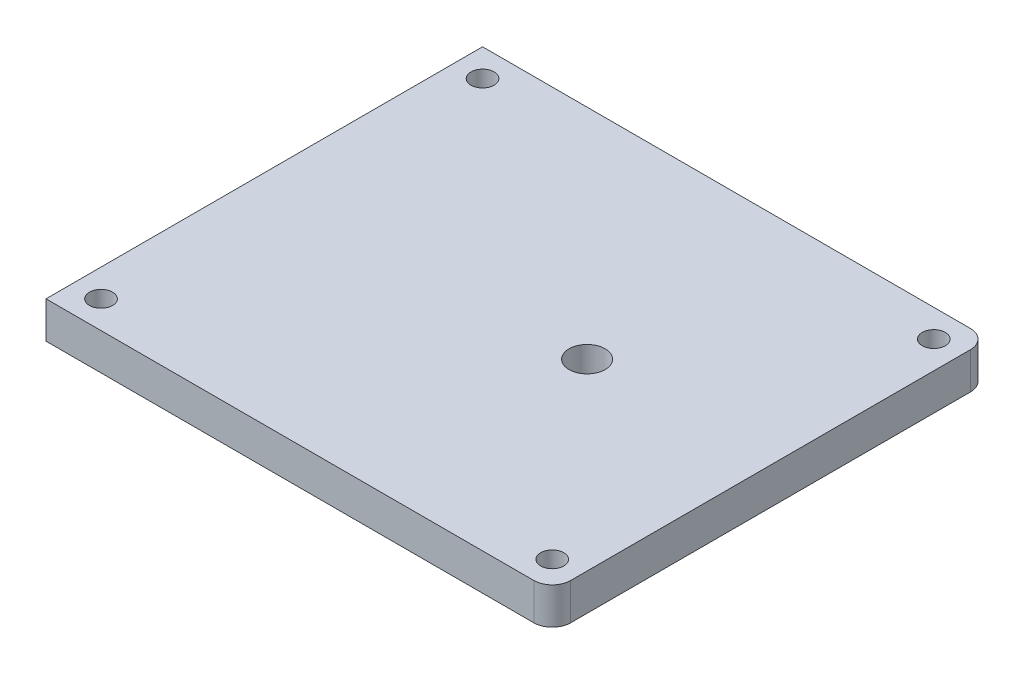
SolidWorks part; units mm, degrees
ref_plane "Front Plane" through (0, 0, 0) normal (0, 0, 1) x (1, 0, 0)
ref_plane "Top Plane" through (0, 0, 0) normal (0, 1, 0) x (1, 0, 0)
ref_plane "Right Plane" through (0, 0, 0) normal (1, 0, 0) x (0, 0, -1)
sketch "Sketch1" plane through (0, 0, 0) normal (0, 1, 0) x (1, 0, 0)
  line L1 (13.0392, 23.6617) -> (48.0912, 23.6617)
  line L2 (13.0392, 23.6617) -> (13.0392, -6.5643)
  line L3 (13.0392, -6.5643) -> (48.0912, -6.5643)
  line L4 (48.0912, 23.6617) -> (48.0912, -6.5643)
  dimension "D1" = 35.052
  dimension "D2" = 30.226
extrude "Boss-Extrude1" add sketch "Sketch1" along normal blind 2.54
hole_wizard "Ø1.6 (1.6) Diameter Hole1" positions "Sketch5" profile "Sketch4" hole size "Ø1.6" standard "ANSI Metric" end condition through all
sketch "Sketch5" plane through (0, 0, 0) normal (0, -1, 0) x (-1, 0, 0)
  line L0 (-48.0912, 23.6617) -> (-13.0392, 23.6617) construction
  line L1 (-13.0392, 23.6617) -> (-13.0392, -6.5643) construction
  line L2 (-48.0912, -6.5643) -> (-48.0912, 23.6617) construction
  line L3 (-13.0392, -6.5643) -> (-48.0912, -6.5643) construction
  point P0 (-14.9442, -4.6593)
  point P2 (-46.1862, -4.6593)
  point P4 (-46.1862, 21.7567)
  point P6 (-14.9442, 21.7567)
  dimension "D1" = 1.905
  dimension "D2" = 1.905
  dimension "D3" = 1.905
  dimension "D4" = 1.905
  dimension "D5" = 1.905
  dimension "D6" = 1.905
  dimension "D7" = 1.905
  dimension "D8" = 1.905
sketch "Sketch4" plane through (14.9442, 0, 4.6593) normal (1, 0, 0) x (0, 0, -1)
  line L0 (0, 0) -> (0, 2.54)
  line L1 (0, 2.54) -> (0.8, 2.54)
  line L2 (0.8, 2.54) -> (0.8, 0)
  line L5 (0.8, 0) -> (0, 0)
  line L11 (0, -6.35) -> (0, 107.95) construction
  dimension "Thru Hole Dia." = 1.6
  dimension "Thru Hole Depth" = 2.54
hole_wizard "Ø2.5 (2.5) Diameter Hole1" positions "Sketch8" profile "Sketch7" hole size "Ø2.5" standard "ANSI Metric" end condition through all
sketch "Sketch8" plane through (0, 2.54, 0) normal (0, 1, 0) x (1, 0, 0)
  line L1 (13.0392, -6.5643) -> (48.0912, -6.5643) construction
  line L2 (48.0912, -6.5643) -> (48.0912, 23.6617) construction
  point P0 (35.3912, 8.5487)
  dimension "D1" = 15.113
  dimension "D2" = 12.7
sketch "Sketch7" plane through (35.3912, 2.54, -8.5487) normal (1, 0, 0) x (0, 0, 1)
  line L0 (0, 0) -> (0, 2.54)
  line L1 (0, 2.54) -> (1.25, 2.54)
  line L2 (1.25, 2.54) -> (1.25, 0)
  line L5 (1.25, 0) -> (0, 0)
  line L11 (0, -6.35) -> (0, 107.95) construction
  dimension "Thru Hole Dia." = 2.5
  dimension "Thru Hole Depth" = 2.54
fillet "Fillet1" radius 1.27 2 edges at (48.0912, 1.27, -23.6617) (48.0912, 1.27, 6.5643)
